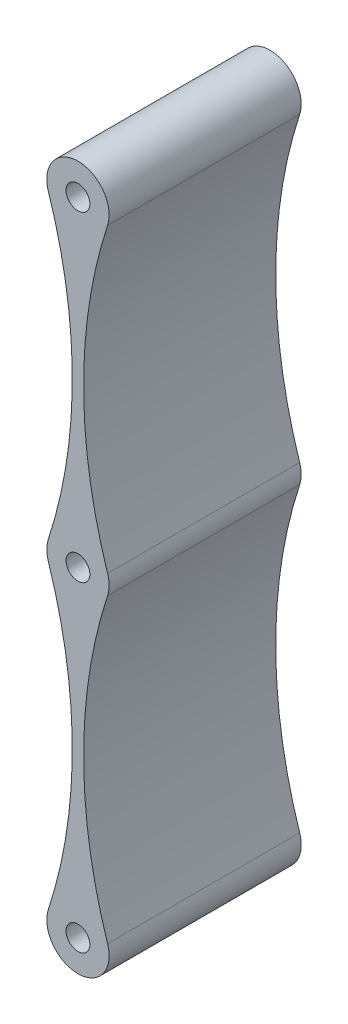
SolidWorks part; units mm, degrees
ref_plane "Front Plane" through (0, 0, 0) normal (0, 0, 1) x (1, 0, 0)
ref_plane "Top Plane" through (0, 0, 0) normal (0, 1, 0) x (1, 0, 0)
ref_plane "Right Plane" through (0, 0, 0) normal (1, 0, 0) x (0, 0, -1)
sketch "Sketch2" plane through (0, 0, 0) normal (0, 0, 1) x (1, 0, 0)
  line L0 (0, 0) -> (0, 2) construction
  line L1 (0, 0) -> (0, 2) construction
  line L2 (-17.6, -134.2) -> (17.6, -134.2) construction
  line L3 (0, -134.2) -> (0, 0) construction
  line L4 (0, -67.1) -> (0, -5) construction
  line L5 (-17.6, 60.8) -> (-17.6, -134.2)
  line L6 (17.6, -134.2) -> (17.6, 60.8)
  line L7 (-65, -309.2) -> (65, -309.2)
  line L8 (-17.6, 60.8) -> (-17.6, -134.2) construction
  line L9 (17.6, -134.2) -> (17.6, 60.8) construction
  line L10 (-65, -309.2) -> (65, -309.2) construction
  line L11 (0, -67.1) -> (0, -129.2) construction
  circle A0 centre (0, -67.1) radius 5.5
  circle A1 centre (0, 60.8) radius 12.6
  circle A2 centre (0, 60.8) radius 12.6 construction
  circle A3 centre (0, -67.1) radius 2.1
  circle A4 centre (0, -211.2176) radius 2.1 construction
  arc A5 (17.6, 60.8) -> (-17.6, 60.8) centre (0, 60.8) ccw
  arc A6 (17.6, -134.2) -> (65, -309.2) centre (364.3485, -134.2) ccw
  arc A7 (-65, -309.2) -> (-17.6, -134.2) centre (-364.3485, -134.2) ccw
  arc A8 (17.6, 60.8) -> (-17.6, 60.8) centre (0, 60.8) ccw construction
  arc A9 (17.6, -134.2) -> (65, -309.2) centre (364.3485, -134.2) ccw construction
  arc A10 (-65, -309.2) -> (-17.6, -134.2) centre (-364.3485, -134.2) ccw construction
  circle A11 centre (0, -211.2176) radius 5.5 construction
  circle A12 centre (0, -10.5) radius 5.5
  circle A13 centre (0, -123.7) radius 5.5
  circle A14 centre (0, -10.5) radius 2.1
  circle A15 centre (0, -123.7) radius 2.1
  arc A16 (-5.2287, -65.394) -> (-5.2287, -12.206) centre (-86.7378, -38.8) ccw
  arc A17 (-5.2287, -121.994) -> (-5.2287, -68.806) centre (-86.7378, -95.4) ccw
  arc A18 (5.2287, -121.994) -> (5.2287, -68.806) centre (86.7378, -95.4) cw
  arc A19 (5.2287, -65.394) -> (5.2287, -12.206) centre (86.7378, -38.8) cw
  point P12 (0, -67.1)
  point P37 (-1, -38.8)
  dimension "D3" = 5
  dimension "D4" = 2
  dimension "D1" = 0
  dimension "D2" = 0
sketch "Sketch4" plane through (0, 0, 0) normal (0, 0, 1) x (1, 0, 0)
  arc A0 (5.2287, -12.206) -> (5.2287, -65.394) centre (86.7378, -38.8) ccw construction
  circle A1 centre (0, -123.7) radius 2.1
  circle A2 centre (0, -123.7) radius 2.1
  circle A3 centre (0, -10.5) radius 2.1
  circle A4 centre (0, -10.5) radius 2.1
  circle A5 centre (0, -123.7) radius 5.5
  arc A6 (-5.2287, -121.994) -> (5.2287, -121.994) centre (0, -123.7) ccw
  circle A7 centre (0, -10.5) radius 5.5
  arc A8 (5.2287, -12.206) -> (-5.2287, -12.206) centre (0, -10.5) ccw
  circle A9 centre (0, -67.1) radius 2.1
  circle A10 centre (0, -67.1) radius 2.1
  circle A11 centre (0, -67.1) radius 5.5
  arc A12 (-5.2287, -65.394) -> (-5.2287, -68.806) centre (0, -67.1) ccw
  arc A13 (5.2287, -68.806) -> (5.2287, -121.994) centre (86.7378, -95.4) ccw construction
  arc A14 (-5.2287, -121.994) -> (-5.2287, -68.806) centre (-86.7378, -95.4) ccw construction
  arc A15 (-5.2287, -65.394) -> (-5.2287, -12.206) centre (-86.7378, -38.8) ccw construction
  arc A16 (5.2287, -12.206) -> (5.2287, -65.394) centre (86.7378, -38.8) ccw
  arc A17 (5.2287, -68.806) -> (5.2287, -121.994) centre (86.7378, -95.4) ccw
  arc A18 (-5.2287, -121.994) -> (-5.2287, -68.806) centre (-86.7378, -95.4) ccw
  arc A19 (-5.2287, -65.394) -> (-5.2287, -12.206) centre (-86.7378, -38.8) ccw
  arc A20 (5.2287, -68.806) -> (5.2287, -65.394) centre (0, -67.1) ccw
  dimension "D1" = 0
  dimension "D2" = 0
  dimension "D3" = 0
  dimension "D4" = 0
  dimension "D5" = 0
  dimension "D6" = 0
extrude "Boss-Extrude1" add sketch "Sketch4" along normal up to surface (16.95 mm away) and the other way up to surface (16.95 mm away)
